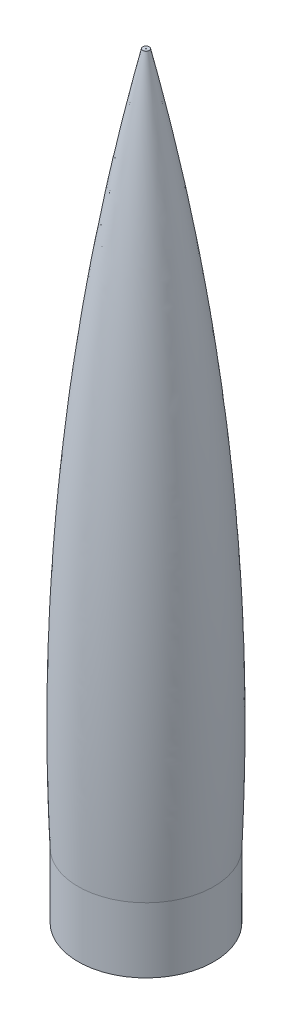
SolidWorks part; units mm, degrees
material "E-Glass Fiber"
ref_plane "Front Plane" through (0, 0, 0) normal (0, 0, 1) x (1, 0, 0)
ref_plane "Top Plane" through (0, 0, 0) normal (0, 1, 0) x (1, 0, 0)
ref_plane "Right Plane" through (0, 0, 0) normal (1, 0, 0) x (0, 0, -1)
sketch "Sketch1" plane through (0, 0, 0) normal (0, 0, 1) x (1, 0, 0)
  line L0 (0, 0) -> (0, 63.133) construction
  line L1 (0, -55) -> (0, 55) construction
  line L2 (2.5146, 539.75) -> (0.254, 539.75)
  line L4 (55, 0) -> (-55, 0) construction
  line L5 (52.9463, 0) -> (50.6857, 0)
  line L6 (0.254, 539.75) -> (27.7927, 328.1374)
  line L7 (27.7927, 328.1374) -> (50.6857, 0)
  spline S0 degree 2 poles (52.9463, 0) (64.1734, 271.1069) (2.5146, 539.75) knots 0 0 0 1 1 1
  dimension "D1" = 2.2606
  dimension "D2" = 50.6857
  dimension "D3" = 539.75
  dimension "D4" = 0.254
revolve "Revolve1" add sketch "Sketch1" angle 360 about L0
sketch "Sketch2" plane through (0, 0, 0) normal (0, -1, 0) x (1, 0, 0)
  circle A0 centre (0, 0) radius 52.9463
  circle A1 centre (0, 0) radius 50.6857
extrude "Boss-Extrude1" add sketch "Sketch2" along normal blind 50.8
